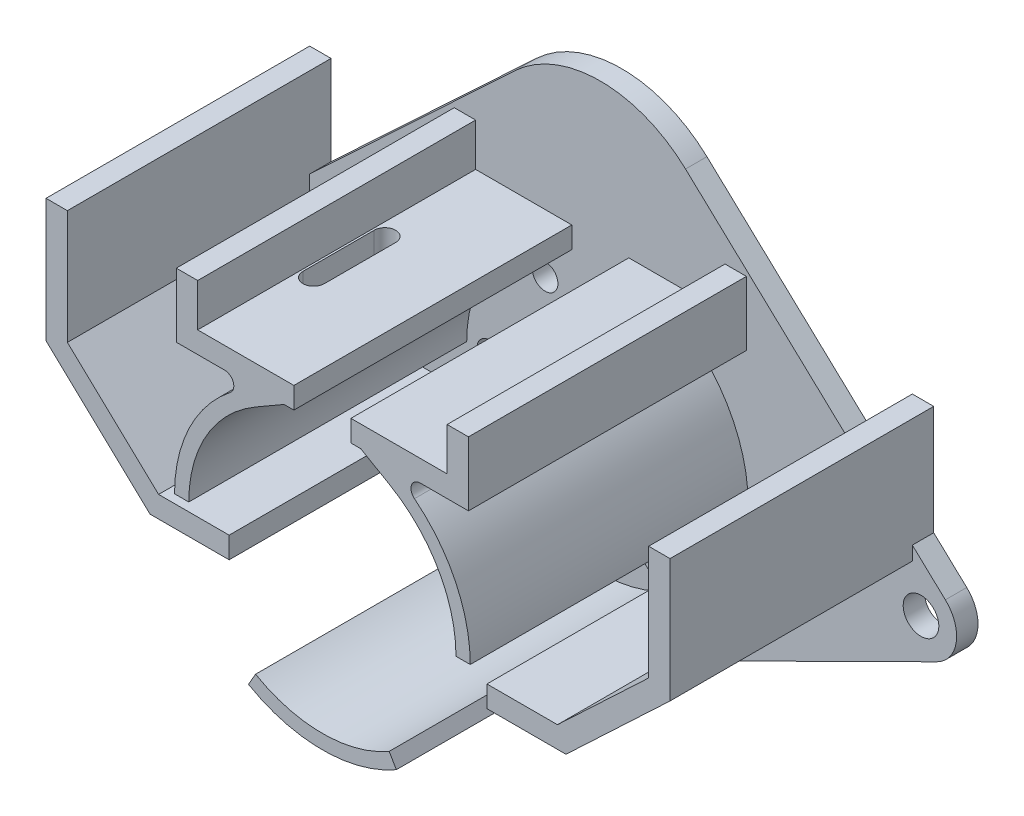
SolidWorks part; units mm, degrees
ref_plane "Front Plane" through (0, 0, 0) normal (0, 0, 1) x (1, 0, 0)
ref_plane "Top Plane" through (0, 0, 0) normal (0, 1, 0) x (1, 0, 0)
ref_plane "Right Plane" through (0, 0, 0) normal (1, 0, 0) x (0, 0, -1)
sketch "Sketch1" plane through (0, 0, 0) normal (0, 0, 1) x (1, 0, 0)
  line L0 (0, 25) -> (0, 0) construction
  line L1 (0, 1.4545) -> (-18.5, 1.4545) construction
  line L2 (-7.75, 14.8779) -> (0, 1.4545) construction
  line L3 (-7.75, -11.9689) -> (0, 1.4545) construction
  line L4 (-45, 0) -> (0, 0) construction
  line L5 (-46.6249, -4.7286) -> (-6.8247, -18.4056) construction
  line L6 (-48.4169, 3.6504) -> (-11.959, 37.7762)
  line L7 (46.6249, -4.7286) -> (6.8247, -18.4056) construction
  line L8 (48.4169, 3.6504) -> (11.959, 37.7762)
  line L9 (-16, -19.5455) -> (16, -19.5455)
  line L10 (-17.6678, -19.1542) -> (-47.2237, -4.4783)
  line L11 (17.6678, -19.1542) -> (47.2237, -4.4783)
  circle A0 centre (-25, 0) radius 2.5
  circle A1 centre (0, 1.4545) radius 18.5 construction
  circle A2 centre (0, -5.5455) radius 6.5
  circle A3 centre (0, 1.4545) radius 15.5 construction
  circle A4 centre (-7.75, 14.8779) radius 1.8
  circle A5 centre (-15.5, 1.4545) radius 1.8
  circle A6 centre (-7.75, -11.9689) radius 1.8
  circle A7 centre (-45, 0) radius 5 construction
  circle A8 centre (0, 25) radius 17.5 construction
  circle A9 centre (0, 1.4545) radius 21 construction
  arc A10 (-48.4169, 3.6504) -> (-46.6249, -4.7286) centre (-45, 0) ccw construction
  circle A11 centre (7.75, -11.9689) radius 1.8
  circle A12 centre (7.75, 14.8779) radius 1.8
  circle A13 centre (15.5, 1.4545) radius 1.8
  circle A14 centre (25, 0) radius 2.5
  arc A15 (48.4169, 3.6504) -> (46.6249, -4.7286) centre (45, 0) cw construction
  arc A16 (-11.959, 37.7762) -> (11.959, 37.7762) centre (0, 25) cw
  arc A17 (6.8247, -18.4056) -> (-6.8247, -18.4056) centre (0, 1.4545) cw construction
  circle A18 centre (-45, 0) radius 2.5
  circle A19 centre (45, 0) radius 2.5
  circle A20 centre (-16, -15.7955) radius 3.75 construction
  circle A21 centre (-16, -15.7955) radius 2.5
  arc A22 (-48.4169, 3.6504) -> (-47.2237, -4.4783) centre (-45, 0) ccw
  arc A23 (-17.6678, -19.1542) -> (-16, -19.5455) centre (-16, -15.7955) ccw
  circle A24 centre (16, -15.7955) radius 3.75 construction
  circle A25 centre (16, -15.7955) radius 2.5
  arc A26 (17.6678, -19.1542) -> (16, -19.5455) centre (16, -15.7955) cw
  arc A27 (48.4169, 3.6504) -> (47.2237, -4.4783) centre (45, 0) cw
  point P53 (0, -19.5455)
  dimension "D1" = 5
  dimension "D2" = 50
  dimension "D3" = 37
  dimension "D5" = 13
  dimension "D9" = 3.6
  dimension "D10" = 31
  dimension "D12" = 10
  dimension "D13" = 35
  dimension "D15" = 42
  dimension "D16" = 5
  dimension "D17" = 7.5
  dimension "D18" = 5
  dimension "D4" = 1.4545
  dimension "D6" = 7
  dimension "D7" = 60
  dimension "D8" = 60
  dimension "D11" = 45
  dimension "D14" = 25
  dimension "D19" = 16
extrude "Boss-Extrude1" add sketch "Sketch1" along normal blind 3
sketch "Sketch2" plane through (0, 0, 3) normal (0, 0, 1) x (1, 0, 0)
  line L0 (0, 0) -> (0, 22.2045) construction
  line L1 (0, 1.4545) -> (-10.375, -16.5155) construction
  line L2 (0, 1.4545) -> (10.375, -16.5155) construction
  line L3 (0, 1.4545) -> (-20.75, 1.4545) construction
  line L4 (0, 1.4545) -> (-10.375, 19.4245) construction
  line L5 (-10.375, 19.4245) -> (-9.375, 17.6925)
  line L6 (-20.75, 1.4545) -> (-18.75, 1.4545)
  line L7 (-10.375, -16.5155) -> (-9.375, -14.7835)
  line L8 (10.375, -16.5155) -> (9.375, -14.7835)
  line L9 (10.375, 19.4245) -> (9.375, 17.6925)
  line L10 (20.75, 1.4545) -> (18.75, 1.4545)
  circle A0 centre (0, 1.4545) radius 18.5 construction
  circle A1 centre (0, 1.4545) radius 18.5 construction
  circle A2 centre (0, 1.4545) radius 18.75 construction
  circle A3 centre (0, 1.4545) radius 20.75 construction
  arc A4 (-20.75, 1.4545) -> (-10.375, 19.4245) centre (0, 1.4545) cw
  arc A5 (-18.75, 1.4545) -> (-9.375, 17.6925) centre (0, 1.4545) cw
  arc A6 (-9.375, -14.7835) -> (9.375, -14.7835) centre (0, 1.4545) ccw
  arc A7 (-10.375, -16.5155) -> (10.375, -16.5155) centre (0, 1.4545) ccw
  arc A8 (20.75, 1.4545) -> (10.375, 19.4245) centre (0, 1.4545) ccw
  arc A9 (18.75, 1.4545) -> (9.375, 17.6925) centre (0, 1.4545) ccw
  dimension "D1" = 37.5
  dimension "D2" = 2
  dimension "D3" = 150
  dimension "D4" = 150
  dimension "D5" = 60
  dimension "D6" = 60
extrude "Boss-Extrude2" add sketch "Sketch2" along normal blind 39 contours L6 A5 L5 A4 | L7 A7 L8 A6 | A9 L10 A8 L9
sketch "Sketch3" plane through (0, 0, 3) normal (0, 0, 1) x (1, 0, 0)
  line L0 (0, 0) -> (0, 23) construction
  line L1 (-12.5, 38) -> (12.5, 38) construction
  line L2 (-12.5, 38) -> (-12.5, 23) construction
  line L3 (-12.5, 23) -> (12.5, 23) construction
  line L4 (12.5, 38) -> (12.5, 23) construction
  line L5 (0, 25) -> (0, 0) construction
  line L6 (-17.5, 29) -> (-17.5, 23)
  line L7 (-17.5, 23) -> (-4, 23)
  line L8 (-4, 23) -> (-4, 20)
  line L9 (-4, 20) -> (-5.3783, 20)
  line L10 (-17.5, 29) -> (-20.5, 29)
  line L11 (-20.5, 29) -> (-20.5, 20)
  line L12 (-20.5, 20) -> (-13.7246, 20)
  line L13 (-9.375, 17.6925) -> (-5.3783, 20)
  line L14 (-12.9186, 17.6925) -> (-9.375, 17.6925)
  arc A0 (-9.375, 17.6925) -> (-18.75, 1.4545) centre (0, 1.4545) ccw construction
  arc A1 (-13.7246, 20) -> (-12.9186, 17.6925) centre (-13.7246, 18.7055) cw
  arc A2 (-10.375, 19.4245) -> (-20.75, 1.4545) centre (0, 1.4545) ccw construction
  dimension "D1" = 25
  dimension "D2" = 15
  dimension "D3" = 23
  dimension "D4" = 8
  dimension "D5" = 3
  dimension "D6" = 35
  dimension "D7" = 3
  dimension "D8" = 6
extrude "Boss-Extrude3" add sketch "Sketch3" along normal up to surface (39 mm away) up to face at (-15.9583, 10.668, 42)
mirror "Mirror1" about plane through (0, 0, 0) normal (1, 0, 0) of "Boss-Extrude3"
sketch "Sketch4" plane through (0, 23, 0) normal (0, 1, 0) x (1, 0, 0)
  line L0 (-13.7246, -42) -> (-13.7246, -3) construction
  line L1 (-13.7246, -42) -> (-13.7246, -3) construction
  line L2 (-15.7246, -17.5) -> (-15.7246, -27.5) construction
  line L3 (-14.2246, -17.5) -> (-14.2246, -27.5)
  line L4 (-17.2246, -17.5) -> (-17.2246, -27.5)
  line L5 (-15.7246, -22.5) -> (-13.7246, -22.5) construction
  line L6 (0, 0) -> (0, -40.251) construction
  line L7 (15.7246, -17.5) -> (15.7246, -27.5) construction
  line L8 (14.2246, -17.5) -> (14.2246, -27.5)
  line L9 (17.2246, -17.5) -> (17.2246, -27.5)
  arc A0 (-14.2246, -17.5) -> (-17.2246, -17.5) centre (-15.7246, -17.5) ccw
  arc A1 (-17.2246, -27.5) -> (-14.2246, -27.5) centre (-15.7246, -27.5) ccw
  arc A2 (14.2246, -17.5) -> (17.2246, -17.5) centre (15.7246, -17.5) cw
  arc A3 (17.2246, -27.5) -> (14.2246, -27.5) centre (15.7246, -27.5) cw
  point P4 (-15.7246, -22.5)
  point P16 (15.7246, -22.5)
  dimension "D1" = 3
  dimension "D2" = 2
  dimension "D3" = 10
extrude "Cut-Extrude1" cut sketch "Sketch4" against normal up to surface (3 mm away) up to face at (-17.1123, 20, 22.5)
sketch "Sketch5" plane through (0, 0, 3) normal (0, 0, 1) x (1, 0, 0)
  line L0 (-43.7844, 23.3468) -> (-43.7844, 6.0404)
  line L1 (-43.7844, 6.0404) -> (-29.1766, -7.7395)
  line L2 (-27.9848, -4.7395) -> (-40.7844, 7.3346)
  line L3 (-40.7844, 7.3346) -> (-40.7844, 23.3468)
  line L4 (-43.7844, 23.3468) -> (-40.7844, 23.3468)
  line L6 (-27.9848, -4.7395) -> (-18.0861, -4.7395)
  line L7 (-29.1766, -7.7395) -> (-18.0861, -7.7395)
  line L8 (-18.0861, -7.7395) -> (-18.0861, -4.7395)
  dimension "D1" = 3
  dimension "D2" = 3
  dimension "D3" = 3
extrude "Boss-Extrude4" add sketch "Sketch5" along normal blind 34
mirror "Mirror2" about plane through (0, 0, 0) normal (1, 0, 0) of "Boss-Extrude4"
sketch "Sketch6" plane through (0, 0, 3) normal (0, 0, -1) x (-1, 0, 0)
  line L4 (40.7844, 23.3468) -> (40.7844, 10.7946)
  line L5 (40.7844, 10.7946) -> (43.7844, 7.9865)
  line L6 (43.7844, 7.9865) -> (43.7844, 23.3468)
  line L7 (43.7844, 23.3468) -> (40.7844, 23.3468)
  line L8 (40.7844, 23.3468) -> (40.7844, 10.7946)
  line L9 (40.7844, 10.7946) -> (43.7844, 7.9865)
  line L10 (43.7844, 7.9865) -> (43.7844, 23.3468)
  line L11 (43.7844, 23.3468) -> (40.7844, 23.3468)
  line L12 (-43.7844, 23.3468) -> (-43.7844, 7.9865)
  line L13 (-43.7844, 7.9865) -> (-40.7844, 10.7946)
  line L14 (-40.7844, 10.7946) -> (-40.7844, 23.3468)
  line L15 (-40.7844, 23.3468) -> (-43.7844, 23.3468)
  line L16 (-43.7844, 23.3468) -> (-43.7844, 7.9865)
  line L17 (-43.7844, 7.9865) -> (-40.7844, 10.7946)
  line L18 (-40.7844, 10.7946) -> (-40.7844, 23.3468)
  line L19 (-40.7844, 23.3468) -> (-43.7844, 23.3468)
  dimension "D1" = 0
  dimension "D2" = 0
extrude "Boss-Extrude5" add sketch "Sketch6" along normal up to surface (3 mm away) up to face at (0, 0.0404, 0)
sketch "Sketch7" plane through (0, 0, 3) normal (0, 0, 1) x (1, 0, 0)
  circle A0 centre (-18.7282, -11.5671) radius 3.75 construction
  circle A1 centre (-18.7282, -11.5671) radius 2.5
  dimension "D1" = 7.5
  dimension "D2" = 5
equation "\"D4@Sketch2\"=\"D3@Sketch2\""
